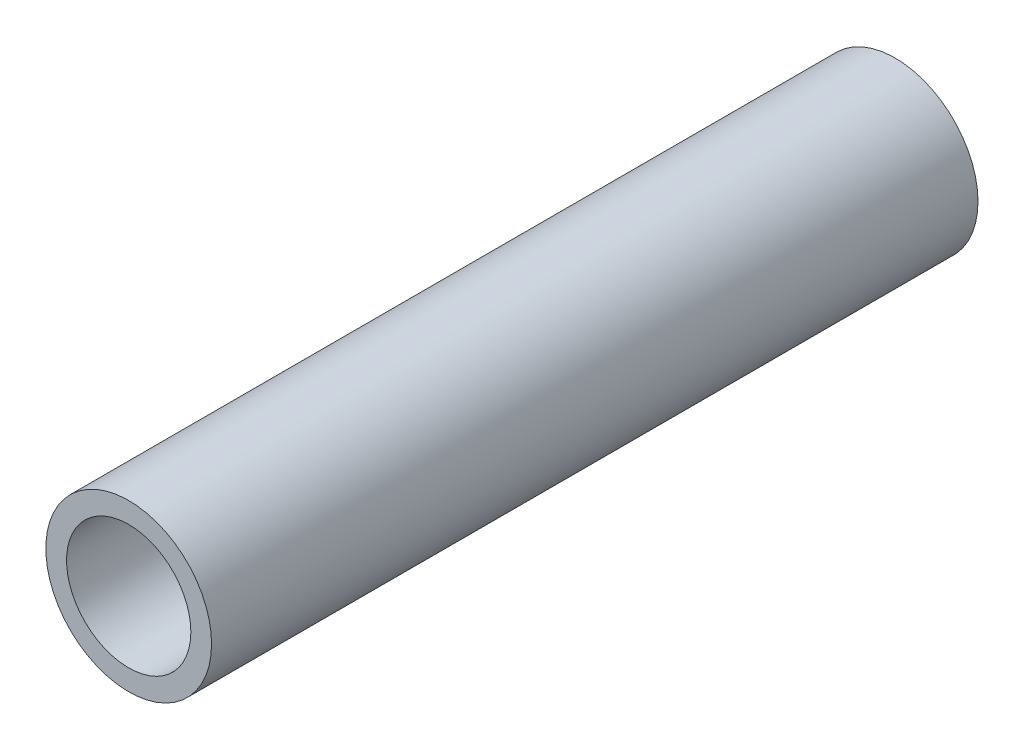
SolidWorks part; units mm, degrees
material "Thornel Mat VMA"
ref_plane "Ön Düzlem" through (0, 0, 0) normal (0, 0, 1) x (1, 0, 0)
ref_plane "Üst Düzlem" through (0, 0, 0) normal (0, 1, 0) x (1, 0, 0)
ref_plane "Sağ Düzlem" through (0, 0, 0) normal (1, 0, 0) x (0, 0, -1)
sketch "Çizim1" plane through (0, 0, 0) normal (0, 0, 1) x (1, 0, 0)
  circle A0 centre (0, 0) radius 8
  circle A1 centre (0, 0) radius 6
extrude "Yükseklik-Ekstrüzyon1" add sketch "Çizim1" along normal blind 74
